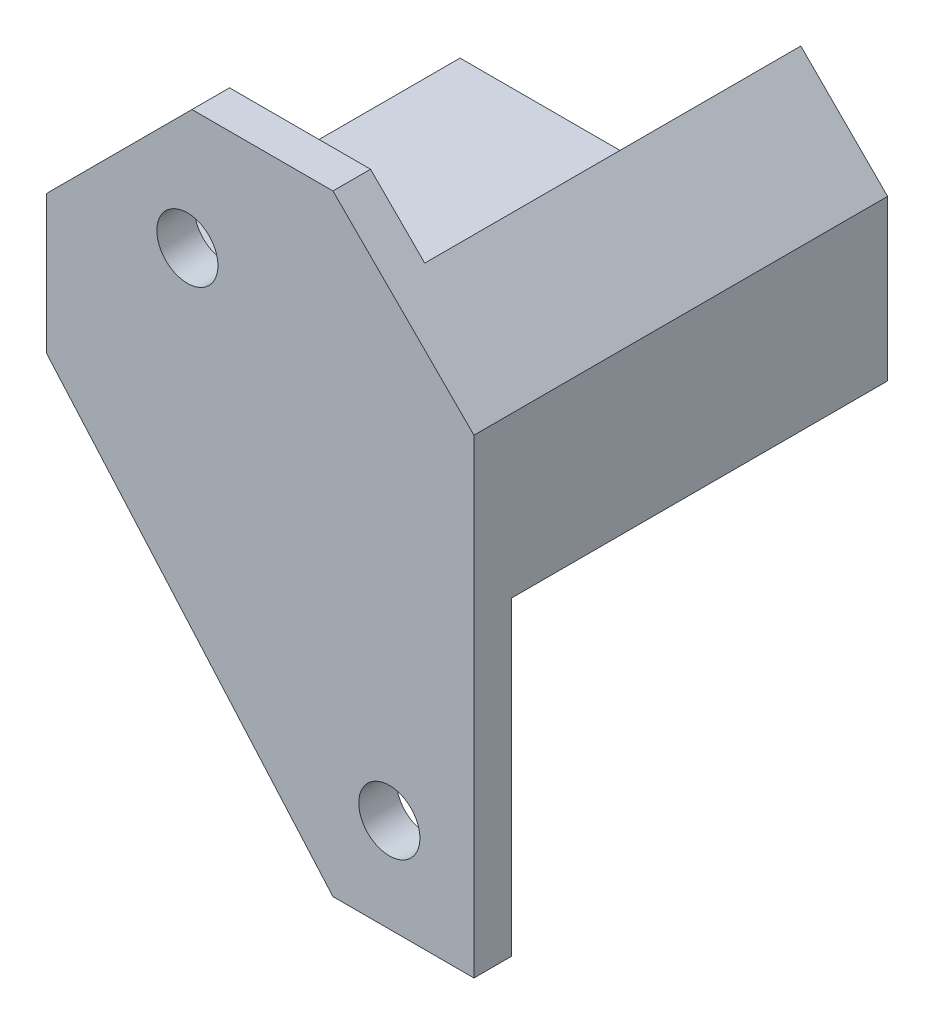
SolidWorks part; units mm, degrees
ref_plane "Front Plane" through (0, 0, 0) normal (0, 0, 1) x (1, 0, 0)
ref_plane "Top Plane" through (0, 0, 0) normal (0, 1, 0) x (1, 0, 0)
ref_plane "Right Plane" through (0, 0, 0) normal (1, 0, 0) x (0, 0, -1)
sketch "Sketch6" plane through (0, 0, 0) normal (0, 0, 1) x (1, 0, 0)
  line L0 (-13.8412, 21.1656) -> (36.1588, 21.1656)
  line L1 (36.1588, 21.1656) -> (36.1588, -43.8344)
  line L2 (36.1588, -43.8344) -> (21.1588, -43.8344)
  line L3 (21.1588, -43.8344) -> (-13.8412, -3.8344)
  line L4 (-13.8412, -3.8344) -> (-13.8412, 21.1656)
  dimension "D1" = 65
  dimension "D2" = 50
  dimension "D3" = 15
  dimension "D4" = 25
extrude "Boss-Extrude4" add sketch "Sketch6" along normal blind 4 contours L0 L1 L2 L3 L4
sketch "Sketch8" plane through (0, 0, 0) normal (0, 0, -1) x (-1, 0, 0)
  line L0 (13.8412, -3.8344) -> (13.8412, 21.1656)
  line L1 (-21.1588, -43.8344) -> (13.8412, -3.8344) construction
  line L2 (13.8412, 21.1656) -> (-36.1588, 21.1656) construction
  line L3 (13.8412, 21.1656) -> (-36.1588, 21.1656)
  line L4 (-36.1588, 21.1656) -> (-36.1588, -28.8344)
  line L5 (-36.1588, 21.1656) -> (-36.1588, -43.8344) construction
  line L6 (-36.1588, -28.8344) -> (-8.0338, -28.8344)
  line L7 (-8.0338, -28.8344) -> (13.8412, -3.8344)
  dimension "D1" = 50
  dimension "D2" = 50
extrude "Boss-Extrude5" add sketch "Sketch8" along normal blind 40 contours L0 L3 L4 L6 L7
chamfer "Chamfer2" distance 20 angle 45 1 edges at (-13.8412, 21.1656, -18)
chamfer "Chamfer3" distance 18 angle 45 1 edges at (36.1588, -28.8344, -20)
chamfer "Chamfer4" distance 15 angle 45 1 edges at (36.1588, 21.1656, -18)
sketch "Sketch9" plane through (-13.8412, 0, 0) normal (-1, 0, 0) x (0, 0, 1)
  circle A0 centre (-26, -16.0013) radius 4.2
extrude "Cut-Extrude3" cut sketch "Sketch9" against normal blind 30
sketch "Sketch12" plane through (0, 0, -40) normal (0, 0, -1) x (-1, 0, 0)
  line L0 (-18.1588, -28.8344) -> (-8.0338, -28.8344) construction
  line L1 (-10.1588, -12.9846) -> (-14.3588, -15.4095)
  line L2 (-14.3588, -15.4095) -> (-14.3588, -20.2592)
  line L3 (-14.3588, -20.2592) -> (-10.1588, -22.6841)
  line L4 (-10.1588, -22.6841) -> (-5.9588, -20.2592)
  line L5 (-5.9588, -20.2592) -> (-5.9588, -15.4095)
  line L6 (-5.9588, -15.4095) -> (-10.1588, -12.9846)
  line L8 (13.8412, -3.8344) -> (13.8412, 1.1656) construction
  circle A0 centre (-10.1588, -17.8344) radius 4.2 construction
  dimension "D1" = 11
  dimension "D2" = 24
sketch "Sketch13" plane through (0, 0, -40) normal (0, 0, -1) x (-1, 0, 0)
  line L0 (-6.1588, 21.1656) -> (-26.1588, 21.1656) construction
  line L1 (-26.1588, 2.0154) -> (-30.3588, -0.4095)
  line L2 (-30.3588, -0.4095) -> (-30.3588, -5.2592)
  line L3 (-30.3588, -5.2592) -> (-26.1588, -7.6841)
  line L4 (-26.1588, -7.6841) -> (-21.9588, -5.2592)
  line L5 (-21.9588, -5.2592) -> (-21.9588, -0.4095)
  line L6 (-21.9588, -0.4095) -> (-26.1588, 2.0154)
  line L7 (-36.1588, 11.1656) -> (-36.1588, -10.8344) construction
  circle A0 centre (-26.1588, -2.8344) radius 4.2 construction
  dimension "D1" = 24
  dimension "D2" = 10
extrude "Cut-Extrude5" cut sketch "Sketch12" against normal blind 5
extrude "Cut-Extrude6" cut sketch "Sketch13" against normal blind 5
sketch "Sketch14" plane through (0, 0, -40) normal (0, 0, -1) x (-1, 0, 0)
  line L0 (-26.9247, 15.3998) -> (-7.6905, -3.8344)
  line L1 (-7.6905, -3.8344) -> (13.8412, -3.8344)
  line L2 (13.8412, -3.8344) -> (13.8412, 21.1656)
  line L3 (13.8412, 21.1656) -> (-21.1588, 21.1656)
  line L4 (-36.1588, -10.8344) -> (-18.1588, -28.8344) construction
  line L5 (-21.1588, 21.1656) -> (-26.9247, 15.3998)
  line L6 (-21.1588, 21.1656) -> (-36.1588, 6.1656) construction
extrude "Cut-Extrude7" cut sketch "Sketch14" against normal up to surface (40 mm away) up to face at (23.9338, -31.2344, 0)
sketch "Sketch15" plane through (0, 0, -40) normal (0, 0, -1) x (-1, 0, 0)
  line L1 (17.6692, 6.8524) -> (9.3205, 6.8524)
  line L2 (17.6692, 6.8524) -> (17.6692, -10.0947)
  line L3 (17.6692, -10.0947) -> (9.3205, -10.0947)
  line L4 (9.3205, 6.8524) -> (9.3205, -10.0947)
extrude "Cut-Extrude8" cut sketch "Sketch15" against normal up to surface (44 mm away) up to face at (13.3017, -5.9772, 4)
sketch "Sketch16" plane through (0, 0, 0) normal (0, 0, -1) x (-1, 0, 0)
  line L0 (-36.1588, -10.8344) -> (-36.1588, -43.8344) construction
  line L1 (-36.1588, -43.8344) -> (-21.1588, -43.8344) construction
  line L2 (-21.1588, 21.1656) -> (-6.1588, 21.1656) construction
  line L3 (9.3205, 5.6863) -> (9.3205, -3.8344) construction
  circle A0 centre (-27.1588, -33.8344) radius 3.25
  circle A1 centre (-5.6795, 8.1656) radius 3.25
  dimension "D1" = 9
  dimension "D2" = 10
  dimension "D3" = 13
  dimension "D4" = 15
extrude "Cut-Extrude9" cut sketch "Sketch16" against normal through all
